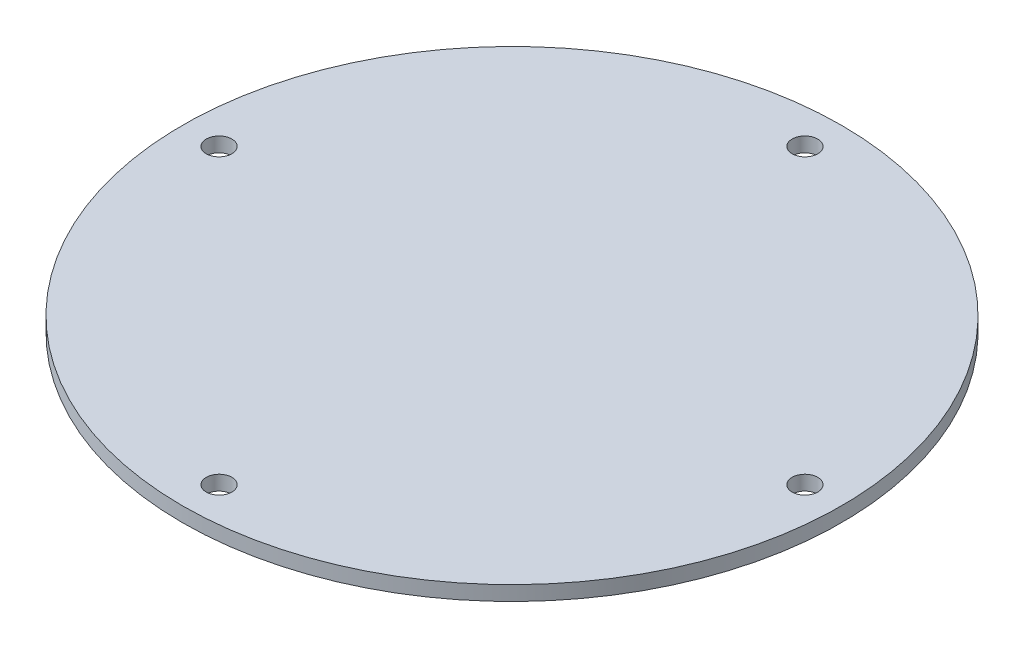
SolidWorks part; units mm, degrees
ref_plane "Front Plane" through (0, 0, 0) normal (0, 0, 1) x (1, 0, 0)
ref_plane "Top Plane" through (0, 0, 0) normal (0, 1, 0) x (1, 0, 0)
ref_plane "Right Plane" through (0, 0, 0) normal (1, 0, 0) x (0, 0, -1)
sketch "Sketch1" plane through (0, 0, 0) normal (0, 1, 0) x (1, 0, 0)
  circle A0 centre (0, 0) radius 45
  dimension "D1" = 90
extrude "Boss-Extrude1" add sketch "Sketch1" along normal blind 2 contours A0
sketch "Sketch2" plane through (0, 2, 0) normal (0, 1, 0) x (1, 0, 0)
  circle A0 centre (0, 40) radius 1.75
  circle A1 centre (40, 0) radius 1.75
  circle A2 centre (0, -40) radius 1.75
  circle A3 centre (-40, 0) radius 1.75
  circle A4 centre (0, 0) radius 45 construction
  point P11 (0, 0)
  dimension "D1" = 40
  dimension "D2" = 3.5
  dimension "D3" = 4
extrude "Cut-Extrude1" cut sketch "Sketch2" against normal through all
